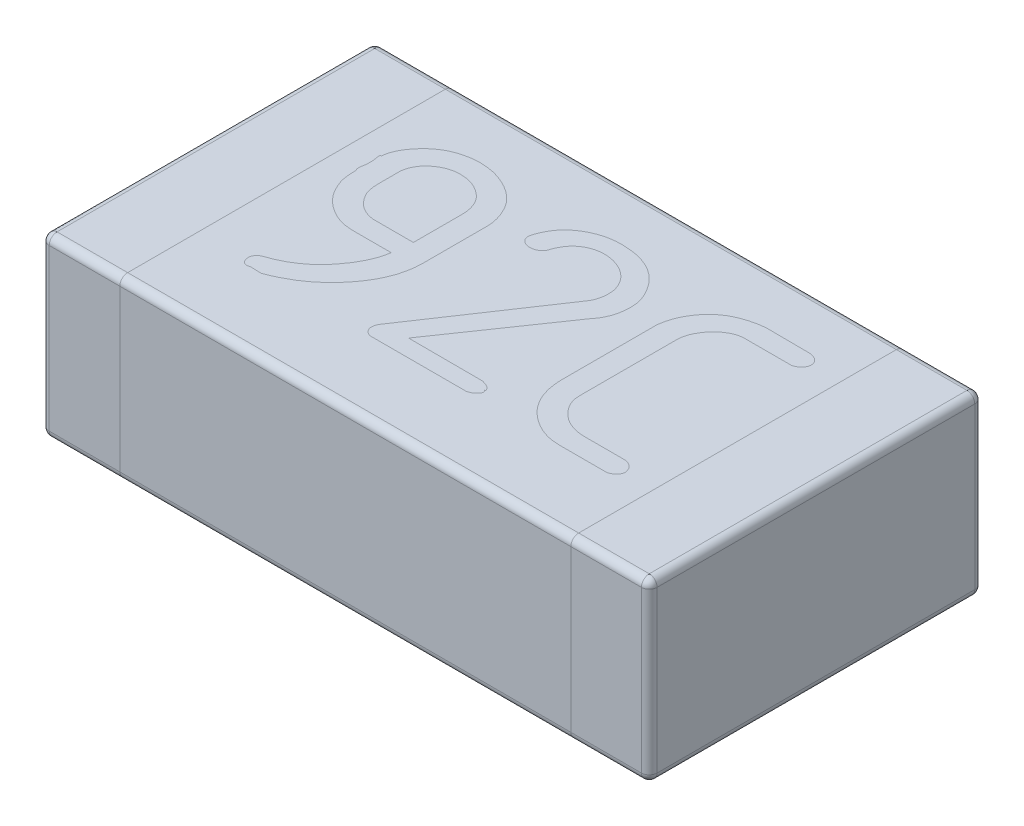
SolidWorks part; units mm, degrees
ref_plane "Front Plane" through (0, 0, 0) normal (0, 0, 1) x (1, 0, 0)
ref_plane "Top Plane" through (0, 0, 0) normal (0, 1, 0) x (1, 0, 0)
ref_plane "Right Plane" through (0, 0, 0) normal (1, 0, 0) x (0, 0, -1)
sketch "Sketch1" plane through (0, 0, 0) normal (0, 1, 0) x (1, 0, 0)
  line L1 (-0.755, -0.425) -> (0.755, -0.425)
  line L2 (-0.775, -0.405) -> (-0.775, 0.405)
  line L3 (-0.755, 0.425) -> (0.755, 0.425)
  line L4 (0.775, -0.405) -> (0.775, 0.405)
  line L5 (-0.775, -0.425) -> (0.775, 0.425) construction
  line L6 (-0.775, 0.425) -> (0.775, -0.425) construction
  arc A4 (-0.775, -0.405) -> (-0.755, -0.425) centre (-0.755, -0.405) ccw
  arc A5 (0.755, -0.425) -> (0.775, -0.405) centre (0.755, -0.405) ccw
  arc A6 (0.775, 0.405) -> (0.755, 0.425) centre (0.755, 0.405) ccw
  arc A7 (-0.755, 0.425) -> (-0.775, 0.405) centre (-0.755, 0.405) ccw
  point P0 (0, 0)
  dimension "D4" = 0.02
  dimension "D1" = 1.55
  dimension "D2" = 0.85
extrude "Boss-Extrude1" add sketch "Sketch1" along normal mid plane 0.45
sketch "Sketch3" plane through (0, 0.225, 0) normal (0, 1, 0) x (1, 0, 0)
  line L0 (-0.575, 0) -> (0.575, 0) construction
  line L1 (-0.575, -0.5133) -> (-0.575, 0.5133)
  line L2 (0.575, -0.5133) -> (0.575, 0.5133)
  line L3 (0, -0.25) -> (0, 0.25) construction
  line L6 (-0.575, -0.25) -> (0.575, -0.25) construction
  text T0 "<b>92C</b>" font "SWIsop1" height 0.53
  point P4 (0, 0)
  point P8 (-0.575, 0)
  point P11 (0.575, 0)
  point P14 (0, 0)
  point P17 (0, -0.25)
  dimension "D1" = 1.15
  dimension "D2" = 0.5
sketch "Sketch4" plane through (0, 0, 0.425) normal (0, 0, 1) x (1, 0, 0)
  line L0 (-0.575, 0.225) -> (-0.575, -0.5946)
  line L1 (0.575, 0.225) -> (0.575, -0.5946)
sketch "Sketch5" plane through (0, 0, -0.425) normal (0, 0, -1) x (-1, 0, 0)
  line L0 (-0.575, 0.225) -> (-0.575, -0.5946) construction
  line L1 (-0.575, 0.225) -> (-0.575, -0.5946)
  line L2 (0.575, 0.225) -> (0.575, -0.5946) construction
  line L3 (0.575, 0.225) -> (0.575, -0.5946)
sketch "Sketch6" plane through (0, -0.225, 0) normal (0, -1, 0) x (1, 0, 0)
  line L0 (0.575, 0.5133) -> (0.575, -0.5133) construction
  line L1 (-0.575, 0.5133) -> (-0.575, -0.5133) construction
  line L2 (0.575, 0.5133) -> (0.575, -0.5133)
  line L3 (-0.575, 0.5133) -> (-0.575, -0.5133)
split line "Split Line2"
split line "Split Line3"
split line "Split Line4"
split line "Split Line5"
fillet "Fillet2" radius 0.02 24 edges at (-0.665, -0.225, 0.425) (0, -0.225, 0.425) (0.665, -0.225, 0.425) (-0.7691, -0.225, 0.4191) (-0.775, -0.225, 0) (-0.7691, -0.225, -0.4191) (0.665, -0.225, -0.425) (0, -0.225, -0.425) (-0.665, -0.225, -0.425) (0.7691, -0.225, -0.4191) (0.775, -0.225, 0) (0.7691, -0.225, 0.4191) (-0.7691, 0.225, 0.4191) (-0.775, 0.225, 0) (-0.7691, 0.225, -0.4191) (0.665, 0.225, -0.425) (0, 0.225, -0.425) (-0.665, 0.225, -0.425) (0.7691, 0.225, -0.4191) (0.775, 0.225, 0) (0.7691, 0.225, 0.4191) (-0.665, 0.225, 0.425) (0, 0.225, 0.425) (0.665, 0.225, 0.425)
